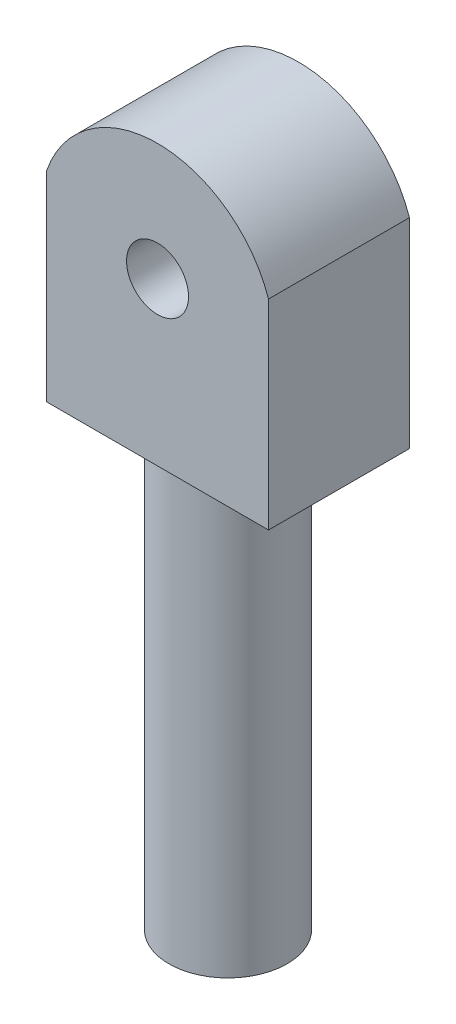
SolidWorks part; units mm, degrees
ref_plane "Front Plane" through (0, 0, 0) normal (0, 0, 1) x (1, 0, 0)
ref_plane "Top Plane" through (0, 0, 0) normal (0, 1, 0) x (1, 0, 0)
ref_plane "Right Plane" through (0, 0, 0) normal (1, 0, 0) x (0, 0, -1)
sketch "Sketch1" plane through (0, 0, 0) normal (0, 0, 1) x (1, 0, 0)
  line L0 (0, 0) -> (0, -21.59)
  line L1 (-4.0005, 21.59) -> (-4.0005, -21.59)
  line L2 (-4.0005, 21.59) -> (4.0005, 21.59)
  line L3 (-4.0005, -21.59) -> (4.0005, -21.59)
  line L4 (4.0005, 21.59) -> (4.0005, -21.59)
  line L5 (-4.0005, 21.59) -> (4.0005, -21.59) construction
  line L6 (-4.0005, -21.59) -> (4.0005, 21.59) construction
  line L7 (-4.0005, 1.3684) -> (4.0005, 1.3684)
  line L8 (-4.0005, -4.629) -> (4.0005, -4.629)
  circle A0 centre (0, 0) radius 1.1176
  circle A1 centre (0, 0) radius 2.3876
  arc A2 (4.0005, 1.3684) -> (-4.0005, 1.3684) centre (0, 0) ccw
  dimension "D1" = 2.2352
  dimension "D2" = 4.7752
  dimension "D3" = 21.59
  dimension "D4" = 8.001
extrude "Boss-Extrude1" add sketch "Sketch1" along normal blind 5.08
sketch "Sketch2" plane through (0, -21.59, 0) normal (0, -1, 0) x (1, 0, 0)
  line L0 (0, 5.08) -> (0, 0)
  line L1 (-4.0005, 5.08) -> (4.0005, 5.08) construction
  line L2 (-4.0005, 2.54) -> (4.0005, 2.54)
  line L3 (-4.0005, 5.08) -> (-4.0005, 0) construction
  line L4 (4.0005, 5.08) -> (4.0005, 0) construction
  circle A0 centre (0, 2.54) radius 1.0922
  dimension "D1" = 2.1844
extrude "Cut-Extrude1" cut sketch "Sketch2" against normal blind 15.748 contours A0
sketch "Sketch3" plane through (0, -21.59, 0) normal (0, -1, 0) x (1, 0, 0)
  line L0 (0, 2.54) -> (2.1318, 2.54)
  circle A0 centre (0, 2.54) radius 2.1318
  line M2 (-4.0005, 0) -> (4.0005, 0)
  line M3 (4.0005, 0) -> (4.0005, 5.08)
  line M4 (4.0005, 5.08) -> (-4.0005, 5.08)
  line M5 (-4.0005, 5.08) -> (-4.0005, 0)
extrude "Cut-Extrude2" cut sketch "Sketch3" against normal blind 15.748 contours A0 M5 M2 M3 M4
sketch "Sketch4" plane through (0, 0, 5.08) normal (0, 0, 1) x (1, 0, 0)
  circle A0 centre (0, 0) radius 2.3876
  dimension "D1" = 4.7752
